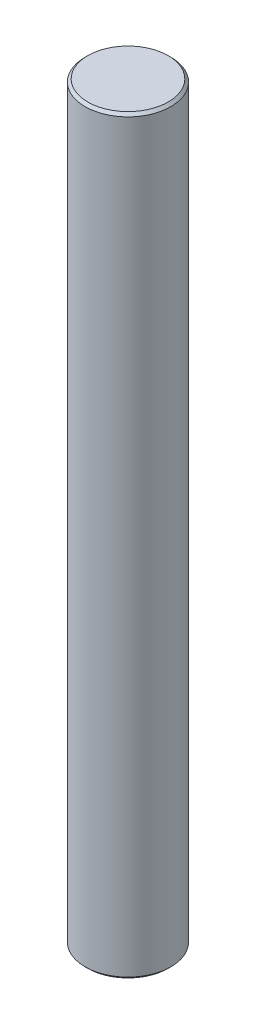
SolidWorks part; units mm, degrees
material "AISI 304"
ref_plane "Front Plane" through (0, 0, 0) normal (0, 0, 1) x (1, 0, 0)
ref_plane "Top Plane" through (0, 0, 0) normal (0, 1, 0) x (1, 0, 0)
ref_plane "Right Plane" through (0, 0, 0) normal (1, 0, 0) x (0, 0, -1)
sketch "Sketch1" plane through (0, 0, 0) normal (0, 1, 0) x (1, 0, 0)
  circle A0 centre (0, 0) radius 4
  dimension "D1" = 8
extrude "Boss-Extrude1" add sketch "Sketch1" along normal blind 70
chamfer "Chamfer1" distance 0.25 angle 45 2 edges at (0, 0, 4) (0, 70, 4)
